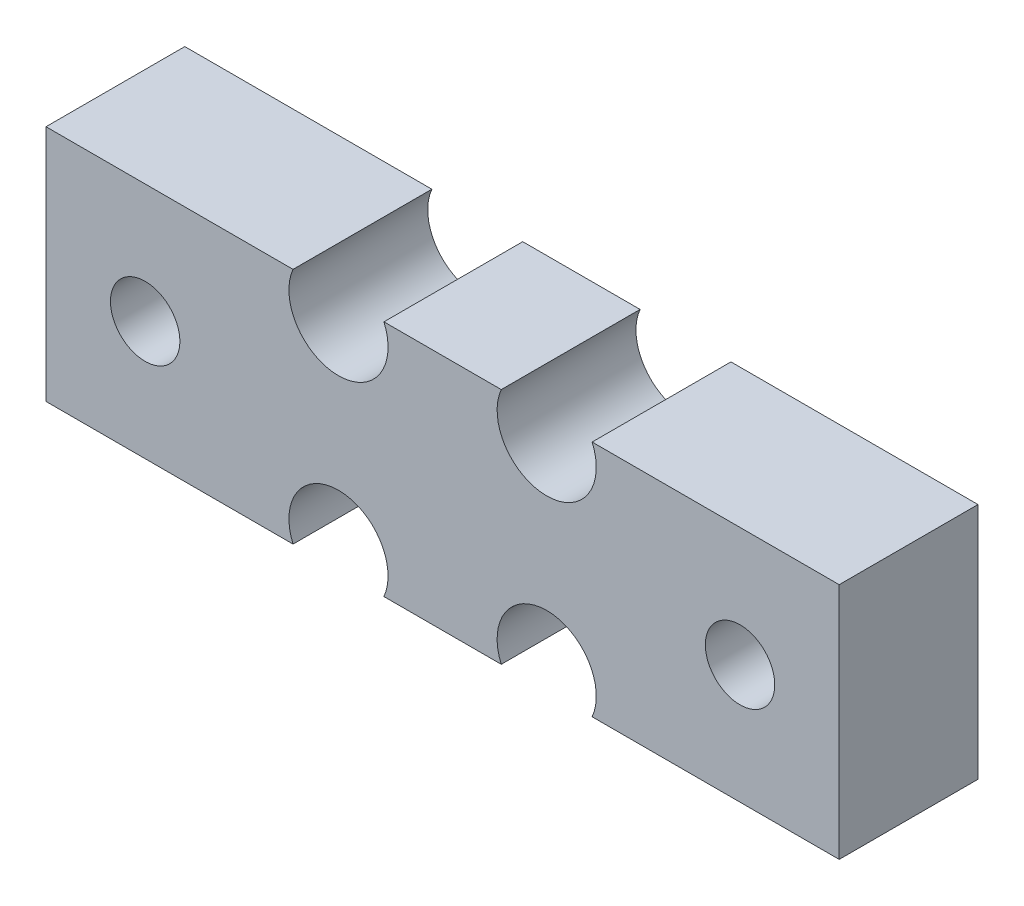
SolidWorks part; units mm, degrees
ref_plane "Front Plane" through (0, 0, 0) normal (0, 0, 1) x (1, 0, 0)
ref_plane "Top Plane" through (0, 0, 0) normal (0, 1, 0) x (1, 0, 0)
ref_plane "Right Plane" through (0, 0, 0) normal (1, 0, 0) x (0, 0, -1)
sketch "Sketch1" plane through (0, 0, 0) normal (0, 0, 1) x (1, 0, 0)
  line L1 (-20, 6) -> (20, 6)
  line L2 (-20, 6) -> (-20, -6)
  line L3 (-20, -6) -> (20, -6)
  line L4 (20, 6) -> (20, -6)
  line L5 (-20, 6) -> (20, -6) construction
  line L6 (-20, -6) -> (20, 6) construction
  point P0 (0, 0)
  dimension "D1" = 40
  dimension "D2" = 12
extrude "Boss-Extrude1" add sketch "Sketch1" along normal blind 7
sketch "Sketch2" plane through (0, 0, 0) normal (0, 0, -1) x (-1, 0, 0)
  line L1 (20, -6) -> (-20, -6) construction
  line L3 (20, 6) -> (20, -6) construction
  line L4 (-20, -6) -> (-20, 6) construction
  circle A0 centre (-5.25, 5) radius 2.5
  circle A1 centre (5.25, 5) radius 2.5
  circle A2 centre (-5.25, -5) radius 2.5
  circle A3 centre (5.25, -5) radius 2.5
  circle A4 centre (-15, 0) radius 1.75
  circle A5 centre (15, 0) radius 1.75
  dimension "D1" = 5
  dimension "D2" = 5
  dimension "D3" = 5
  dimension "D4" = 5
  dimension "D5" = 10
  dimension "D6" = 10
  dimension "D7" = 1
  dimension "D8" = 1
  dimension "D9" = 10.5
  dimension "D10" = 10.5
  dimension "D11" = 14.75
  dimension "D12" = 3.5
  dimension "D13" = 3.5
  dimension "D14" = 5
  dimension "D15" = 5
extrude "Cut-Extrude1" cut sketch "Sketch2" against normal blind 7
